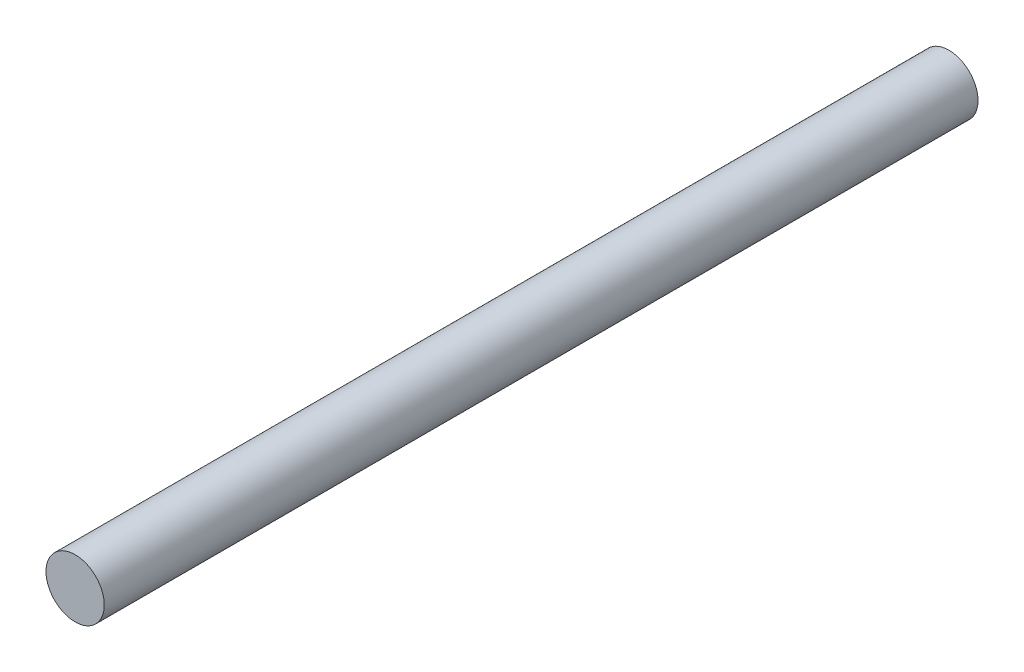
SolidWorks part; units mm, degrees
ref_plane "Front Plane" through (0, 0, 0) normal (0, 0, 1) x (1, 0, 0)
ref_plane "Top Plane" through (0, 0, 0) normal (0, 1, 0) x (1, 0, 0)
ref_plane "Right Plane" through (0, 0, 0) normal (1, 0, 0) x (0, 0, -1)
sketch "Sketch1" plane through (0, 0, 0) normal (0, 0, 1) x (1, 0, 0)
  circle A0 centre (0, 0) radius 3
  dimension "D1" = 6
extrude "Boss-Extrude1" add sketch "Sketch1" along normal blind 90
